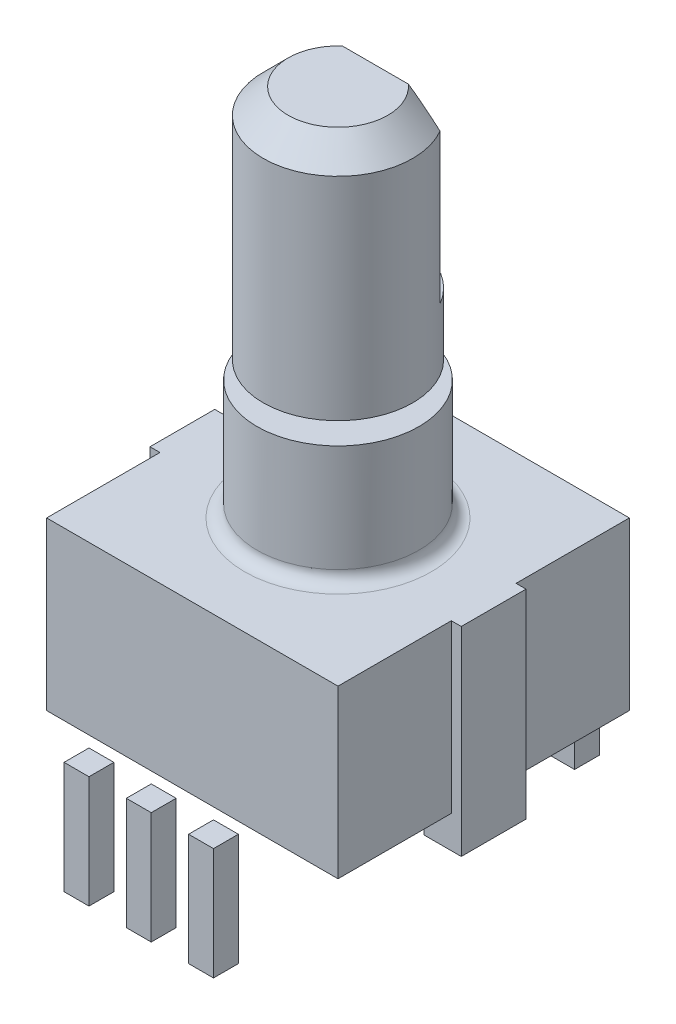
SolidWorks part; units mm, degrees
ref_plane "Front Plane" through (0, 0, 0) normal (0, 0, 1) x (1, 0, 0)
ref_plane "Top Plane" through (0, 0, 0) normal (0, 1, 0) x (1, 0, 0)
ref_plane "Right Plane" through (0, 0, 0) normal (1, 0, 0) x (0, 0, -1)
sketch "Sketch1" plane through (0, 0, 0) normal (0, 1, 0) x (1, 0, 0)
  line L1 (-5.85, -5.85) -> (5.85, -5.85)
  line L2 (-5.85, -5.85) -> (-5.85, 5.85)
  line L3 (-5.85, 5.85) -> (5.85, 5.85)
  line L4 (5.85, -5.85) -> (5.85, 5.85)
  line L5 (-5.85, -5.85) -> (5.85, 5.85) construction
  line L6 (-5.85, 5.85) -> (5.85, -5.85) construction
  point P0 (0, 0)
  dimension "D1" = 11.7
  dimension "D2" = 11.7
extrude "Boss-Extrude1" add sketch "Sketch1" against normal blind 6.7
sketch "Sketch2" plane through (0, 0, 0) normal (0, 1, 0) x (1, 0, 0)
  circle A0 centre (0, 0) radius 3.25
  dimension "D1" = 6.5
extrude "Boss-Extrude2" add sketch "Sketch2" along normal blind 4.8
fillet "Fillet1" radius 0.5 1 edges at (0, 0, 3.25)
sketch "Sketch3" plane through (0, 4.8, 0) normal (0, 1, 0) x (1, 0, 0)
  circle A0 centre (0, 0) radius 2
  dimension "D1" = 4
extrude "Boss-Extrude3" add sketch "Sketch3" along normal blind 0.7
sketch "Sketch4" plane through (0, 5.5, 0) normal (0, 1, 0) x (1, 0, 0)
  circle A0 centre (0, 0) radius 3
  dimension "D1" = 6
extrude "Boss-Extrude4" add sketch "Sketch4" along normal blind 9.5
sketch "Sketch5" plane through (0, 15, 0) normal (0, 1, 0) x (1, 0, 0)
  line L0 (-2.5981, 1.5) -> (2.5981, 1.5)
  circle A0 centre (0, 0) radius 3 construction
  arc A1 (-2.5981, 1.5) -> (2.5981, 1.5) centre (0, 0) cw
  dimension "D1" = 1.5
extrude "Cut-Extrude1" cut sketch "Sketch5" against normal blind 7
sketch "Sketch6" plane through (0, 0, 0) normal (0, 1, 0) x (1, 0, 0)
  line L1 (-3, 6.5) -> (-2, 6.5)
  line L2 (-3, 6.5) -> (-3, 7.5)
  line L3 (-3, 7.5) -> (-2, 7.5)
  line L4 (-2, 6.5) -> (-2, 7.5)
  line L6 (3, 6.5) -> (2, 6.5)
  line L7 (3, 6.5) -> (3, 7.5)
  line L8 (3, 7.5) -> (2, 7.5)
  line L9 (2, 6.5) -> (2, 7.5)
  line L10 (-0.5, -7) -> (0.5, -7)
  line L11 (-0.5, -7) -> (-0.5, -8)
  line L12 (-0.5, -8) -> (0.5, -8)
  line L13 (0.5, -7) -> (0.5, -8)
  line L15 (3, -7) -> (2, -7)
  line L16 (3, -7) -> (3, -8)
  line L17 (3, -8) -> (2, -8)
  line L18 (2, -7) -> (2, -8)
  line L19 (-3, -7) -> (-2, -7)
  line L20 (-3, -7) -> (-3, -8)
  line L21 (-3, -8) -> (-2, -8)
  line L22 (-2, -7) -> (-2, -8)
  point P4 (-3, 7)
  point P14 (-3, -7.5)
  point P24 (0, -8)
  point P26 (2.5, 7.5)
  point P27 (-2.5, 7.5)
  dimension "D1" = 1
  dimension "D2" = 2.5
  dimension "D3" = 2.5
  dimension "D4" = 1
  dimension "D5" = 7.5
  dimension "D6" = 7
extrude "Boss-Extrude5" add sketch "Sketch6" against normal blind 4.5 from offset 6 separate body offset against normal yes
sketch "Sketch8" plane through (0, 0, 0) normal (0, 1, 0) x (1, 0, 0)
  line L1 (-6.25, -1.3) -> (-4.75, -1.3)
  line L2 (-6.25, -1.3) -> (-6.25, 1.3)
  line L3 (-6.25, 1.3) -> (-4.75, 1.3)
  line L4 (-4.75, -1.3) -> (-4.75, 1.3)
  line L5 (-6.25, -1.3) -> (-4.75, 1.3) construction
  line L6 (-6.25, 1.3) -> (-4.75, -1.3) construction
  line L7 (4.75, -1.3) -> (6.25, -1.3)
  line L8 (4.75, -1.3) -> (4.75, 1.3)
  line L9 (4.75, 1.3) -> (6.25, 1.3)
  line L10 (6.25, -1.3) -> (6.25, 1.3)
  line L11 (4.75, -1.3) -> (6.25, 1.3) construction
  line L12 (4.75, 1.3) -> (6.25, -1.3) construction
  point P0 (-5.5, 0)
  point P5 (5.5, 0)
  dimension "D1" = 2.6
  dimension "D2" = 1.5
  dimension "D3" = 6.25
  dimension "D4" = 6.25
extrude "Boss-Extrude6" add sketch "Sketch8" against normal blind 8
chamfer "Chamfer1" distance 1 angle 45 1 edges at (0, 15, 3)
equation "\"D3@Sketch6\"=\"D2@Sketch6\""
